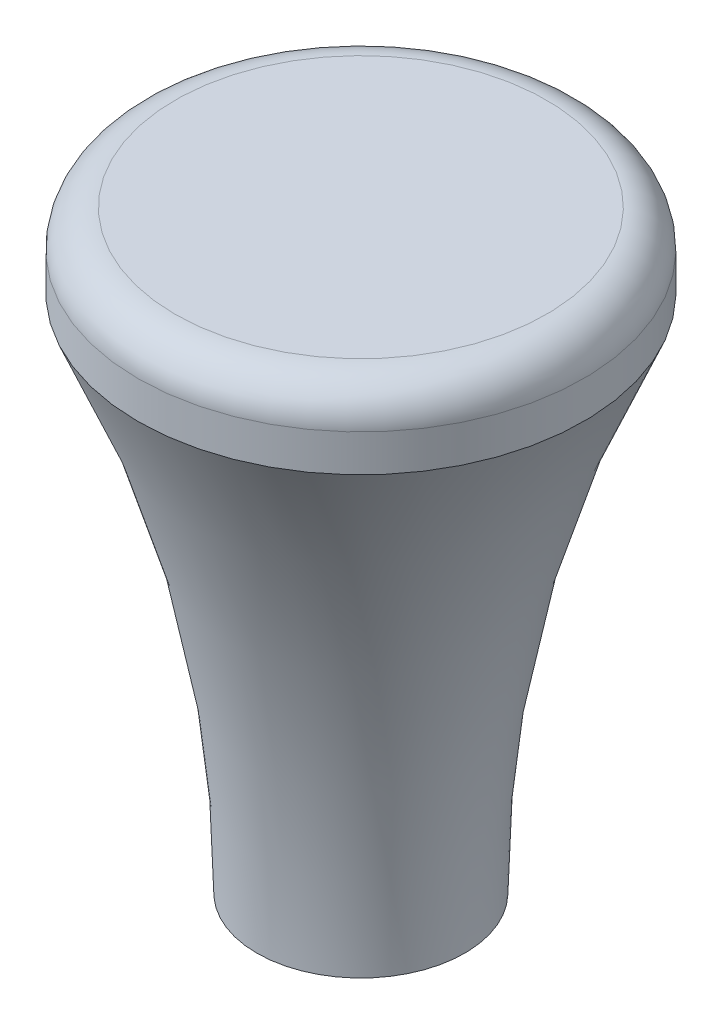
SolidWorks part; units mm, degrees
ref_plane "Front Plane" through (0, 0, 0) normal (0, 0, 1) x (1, 0, 0)
ref_plane "Top Plane" through (0, 0, 0) normal (0, 1, 0) x (1, 0, 0)
ref_plane "Right Plane" through (0, 0, 0) normal (1, 0, 0) x (0, 0, -1)
sketch "Sketch1" plane through (0, 0, 0) normal (1, 0, 0) x (0, 0, -1)
  line L0 (0, 28.85) -> (0, -22.45) construction
  line L1 (-7, -19.2501) -> (0, -19.2501)
  line L2 (-15, 15.7499) -> (-15, 18.2499)
  line L3 (-12.5, 20.7499) -> (0, 20.7499)
  line L4 (0, -19.2501) -> (0, 20.7499)
  arc A0 (-7, -19.2501) -> (-15, 15.7499) centre (-87.5625, -19.2501) ccw
  arc A1 (-12.5, 20.7499) -> (-15, 18.2499) centre (-12.5, 18.2499) ccw
  dimension "D4" = 2.5
  dimension "D1" = 7
  dimension "D2" = 15
  dimension "D3" = 35
  dimension "D5" = 40
revolve "Revolve1" add sketch "Sketch1" angle 360 about L0
sketch "Sketch2" plane through (0, -19.2501, 0) normal (0, -1, 0) x (1, 0, 0)
  line L0 (0, 7) -> (0, -7) construction
  circle A0 centre (0, 0) radius 7 construction
  circle A1 centre (0, 0) radius 1
  dimension "D1" = 2
extrude "Cut-Extrude1" cut sketch "Sketch2" against normal blind 5
